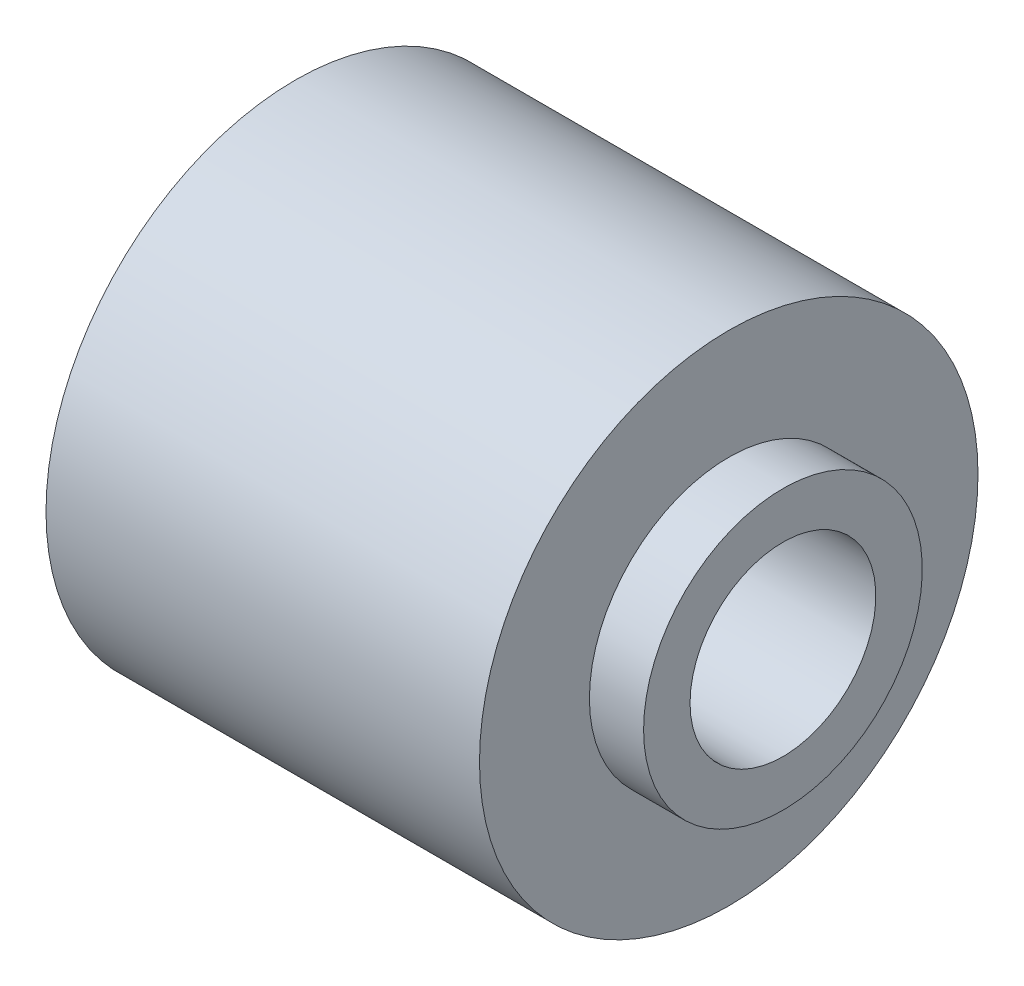
SolidWorks part; units mm, degrees
ref_plane "Płaszczyzna przednia" through (0, 0, 0) normal (0, 0, 1) x (1, 0, 0)
ref_plane "Płaszczyzna górna" through (0, 0, 0) normal (0, 1, 0) x (1, 0, 0)
ref_plane "Płaszczyzna prawa" through (0, 0, 0) normal (1, 0, 0) x (0, 0, -1)
sketch "Szkic1" plane through (0, 0, 0) normal (0, 1, 0) x (1, 0, 0)
  line L0 (-14, 6) -> (-17.5, 6)
  line L1 (-14, 0) -> (14, 0)
  line L3 (-14, 16.1) -> (14, 16.1)
  line L5 (-17.5, 6) -> (-17.5, 9)
  line L6 (-17.5, 9) -> (-14, 9)
  line L7 (14, 16.1) -> (14, 9)
  line L9 (-14, 16.1) -> (-14, 9)
  line L11 (-14, 0) -> (-14, 6)
  line L14 (14, 9) -> (17.5, 9)
  line L15 (17.5, 9) -> (17.5, 6)
  line L16 (17.5, 6) -> (14, 6)
  line L17 (14, 0) -> (14, 6)
  point P4 (0, 0)
  dimension "D2" = 16.1
  dimension "D4" = 14
  dimension "D6" = 17.5
  dimension "D7" = 9
  dimension "D8" = 6
revolve "Obrót1" add sketch "Szkic1" angle 360 about L1
sketch "Szkic2" plane through (-14, 0, 0) normal (-1, 0, 0) x (0, 0, 1)
  circle A1 centre (0, 0) radius 6
  circle A2 centre (0, 0) radius 6
  dimension "D1" = 0
extrude "Wytnij-wyciągnięcie1" cut sketch "Szkic2" against normal up to surface (28 mm away) up to face at (14, 0, 6)
